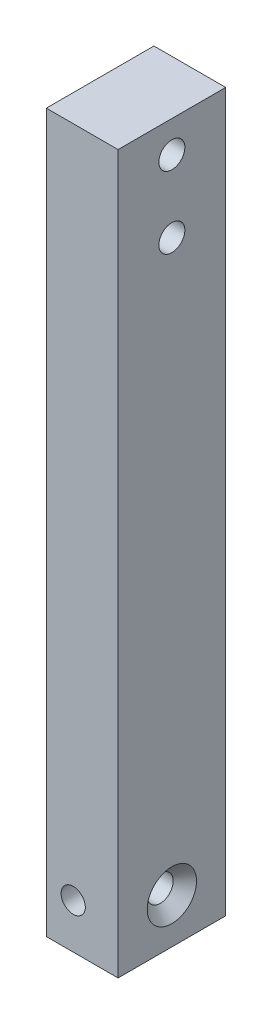
SolidWorks part; units mm, degrees
ref_plane "前基準面" through (0, 0, 0) normal (0, 0, 1) x (1, 0, 0)
ref_plane "上基準面" through (0, 0, 0) normal (0, 1, 0) x (1, 0, 0)
ref_plane "右基準面" through (0, 0, 0) normal (1, 0, 0) x (0, 0, -1)
sketch "草圖1" plane through (0, 0, 0) normal (1, 0, 0) x (0, 0, -1)
  line L1 (-6, -40) -> (6, -40)
  line L2 (-6, -40) -> (-6, 40)
  line L3 (-6, 40) -> (6, 40)
  line L4 (6, -40) -> (6, 40)
  line L5 (-6, -40) -> (6, 40) construction
  line L6 (-6, 40) -> (6, -40) construction
  point P0 (0, 0)
  dimension "D1" = 80
  dimension "D2" = 12
extrude "填料-伸長1" add sketch "草圖1" along normal blind 8
sketch "草圖2" plane through (0, 0, 0) normal (-1, 0, 0) x (0, 0, 1)
  line L0 (6, -40) -> (-6, -40) construction
  line L1 (0, -35) -> (0, 0) construction
  circle A0 centre (0, -35) radius 3
  dimension "D1" = 6
  dimension "D2" = 5
extrude "除料-伸長1" cut sketch "草圖2" against normal blind 5
hole_wizard "M2.5 錐坑平頭螺釘的錐孔1" positions "草圖3" profile "草圖4" countersink size "M2.5" standard "ISO" end condition through all
sketch "草圖3" plane through (8, 0, 0) normal (1, 0, 0) x (0, 0, -1)
  line L0 (-6, -40) -> (6, -40) construction
  point P0 (0, -35)
  dimension "D1" = 5
sketch "草圖4" plane through (8, -35, 0) normal (0, 1, 0) x (0, 0, -1)
  line L0 (0, 0) -> (0, 8)
  line L1 (0, 8) -> (1.45, 8)
  line L2 (1.45, 8) -> (1.45, 1.3)
  line L3 (1.45, 1.3) -> (2.75, 0)
  line L5 (2.75, 0) -> (0, 0)
  line L6 (-1.45, 1.3) -> (-2.75, 0) construction
  line L11 (0, -6.35) -> (0, 107.95) construction
  dimension "貫穿孔直徑" = 2.9
  dimension "貫穿孔深度" = 8
  dimension "近端錐孔直徑" = 5.5
  dimension "近端錐孔角度" = 90
hole_wizard "M2.5 錐坑平頭螺釘的錐孔2" positions "草圖5" profile "草圖6" countersink size "M2.5" standard "ISO" end condition through all
sketch "草圖5" plane through (0, 0, 0) normal (-1, 0, 0) x (0, 0, 1)
  line L0 (-6, 40) -> (6, 40) construction
  point P0 (0, 36.5)
  point P2 (0, 28.5)
  dimension "D1" = 8
  dimension "D2" = 3.5
sketch "草圖6" plane through (0, 36.5, 0) normal (0, 1, 0) x (0, 0, 1)
  line L0 (0, 0) -> (0, 8)
  line L1 (0, 8) -> (1.45, 8)
  line L2 (1.45, 8) -> (1.45, 1.3)
  line L3 (1.45, 1.3) -> (2.75, 0)
  line L5 (2.75, 0) -> (0, 0)
  line L6 (-1.45, 1.3) -> (-2.75, 0) construction
  line L11 (0, -6.35) -> (0, 107.95) construction
  dimension "貫穿孔直徑" = 2.9
  dimension "貫穿孔深度" = 8
  dimension "近端錐孔直徑" = 5.5
  dimension "近端錐孔角度" = 90
hole_wizard "Ø1.0mm 定位孔2" positions "草圖7" profile "草圖8" hole size "Ø1.0" standard "ISO"
sketch "草圖7" plane through (0, 0, 6) normal (0, 0, 1) x (1, 0, 0)
  line L0 (8, -40) -> (0, -40) construction
  line L1 (0, 40) -> (0, -40) construction
  point P0 (3, -35)
  dimension "D1" = 5
  dimension "D2" = 3
sketch "草圖8" plane through (3, -35, 6) normal (1, 0, 0) x (0, -1, 0)
  line L0 (0, 0) -> (0, 12)
  line L1 (0, 12) -> (1.35, 12)
  line L2 (1.35, 12) -> (1.35, 0)
  line L5 (1.35, 0) -> (0, 0)
  line L11 (0, -6.35) -> (0, 107.95) construction
  dimension "貫穿孔直徑" = 2.7
  dimension "貫穿孔深度" = 12
mirror "鏡射1" about plane through (0, 0, 0) normal (0, 0, 1) of "Ø1.0mm 定位孔2"
